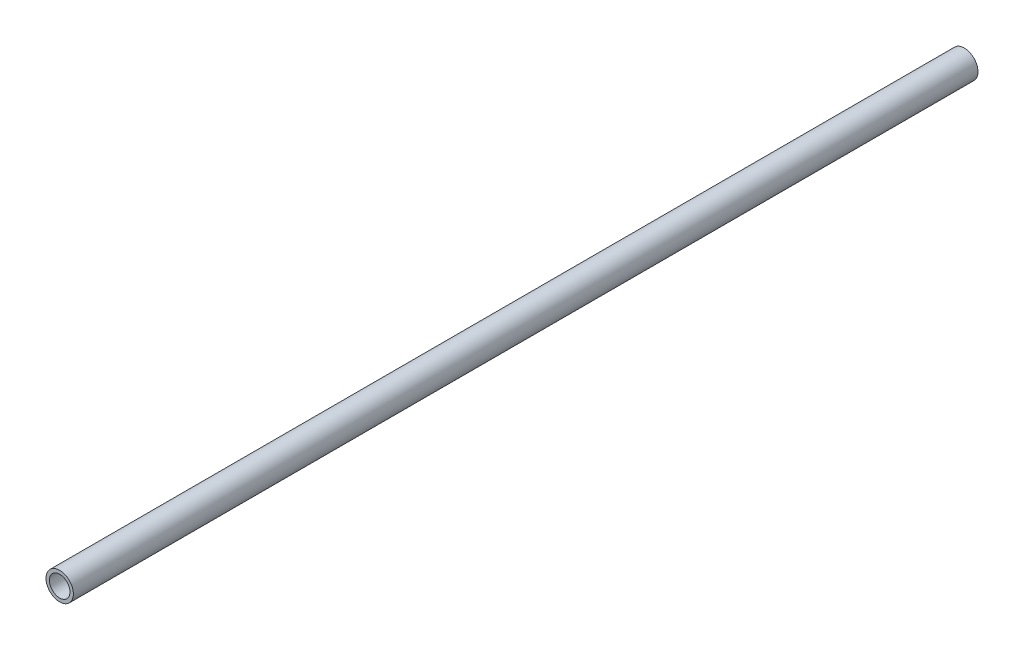
SolidWorks part; units mm, degrees
ref_plane "Front Plane" through (0, 0, 0) normal (0, 0, 1) x (1, 0, 0)
ref_plane "Top Plane" through (0, 0, 0) normal (0, 1, 0) x (1, 0, 0)
ref_plane "Right Plane" through (0, 0, 0) normal (1, 0, 0) x (0, 0, -1)
sketch "Sketch1" plane through (0, 0, 0) normal (0, 0, 1) x (1, 0, 0)
  circle A0 centre (0, 0) radius 14.224
  dimension "D1" = 28.448
extrude "Boss-Extrude1" add sketch "Sketch1" along normal blind 939.8
sketch "Sketch2" plane through (0, 0, 939.8) normal (0, 0, 1) x (1, 0, 0)
  circle A0 centre (0, 0) radius 10.6934
  circle A1 centre (0, 0) radius 14.224 construction
  dimension "D1" = 3.5306
extrude "Cut-Extrude1" cut sketch "Sketch2" against normal through all
